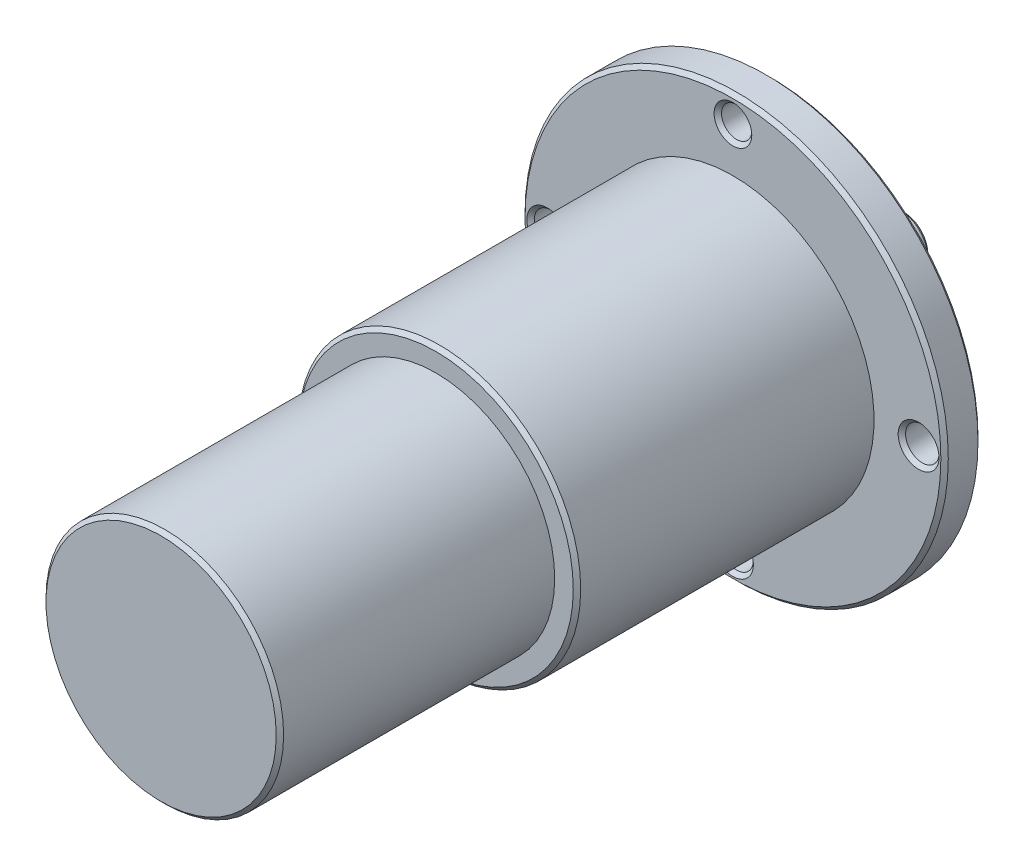
SolidWorks part; units mm, degrees
ref_plane "Front Plane" through (0, 0, 0) normal (0, 0, 1) x (1, 0, 0)
ref_plane "Top Plane" through (0, 0, 0) normal (0, 1, 0) x (1, 0, 0)
ref_plane "Right Plane" through (0, 0, 0) normal (1, 0, 0) x (0, 0, -1)
sketch "Sketch1" plane through (0, 0, 0) normal (0, 1, 0) x (1, 0, 0)
  line L0 (-29.6267, 29.8532) -> (-29.6267, -83.7972) construction
  line L1 (-29.6267, 24.6345) -> (-33.3767, 24.6345)
  line L2 (-33.3767, 9.6345) -> (-42.1267, 9.6345)
  line L3 (-42.1267, 9.6345) -> (-42.1267, 6.6345)
  line L4 (-42.1267, 6.6345) -> (-58.1267, 6.6345)
  line L5 (-58.1267, 6.6345) -> (-58.1267, 1.6345)
  line L6 (-58.1267, 1.6345) -> (-48.6267, 1.6345)
  line L7 (-48.6267, 1.6345) -> (-48.6267, -38.3655)
  line L8 (-48.6267, -38.3655) -> (-45.6267, -38.3655)
  line L9 (-45.6267, -38.3655) -> (-45.6267, -75.3655)
  line L10 (-45.6267, -75.3655) -> (-29.6267, -75.3655)
  line L11 (-33.3767, 24.6345) -> (-33.3767, 9.6345)
  line L12 (-29.6267, 24.6345) -> (-29.6267, -75.3655)
  dimension "D1" = 3.75
  dimension "D2" = 15
  dimension "D3" = 12.5
  dimension "D4" = 28.5
  dimension "D5" = 16
  dimension "D6" = 19
  dimension "D7" = 3
  dimension "D8" = 5
  dimension "D9" = 40
  dimension "D10" = 77
  dimension "D11" = 100
revolve "Revolve1" add sketch "Sketch1" angle 360 about L0
sketch "Sketch2" plane through (0, 0, -1.6345) normal (0, 0, 1) x (1, 0, 0)
  line L0 (-58.1267, 0) -> (-1.1267, 0) construction
  line L1 (-29.6267, 28.5) -> (-29.6267, -28.5) construction
  circle A1 centre (-4.6267, 0) radius 2.25
  circle A2 centre (-29.6267, 25) radius 2.0368
  circle A3 centre (-54.6267, 0) radius 2.25
  circle A4 centre (-29.6267, -25) radius 2.25
  dimension "D2" = 50
  dimension "D1" = 4.5
  dimension "D3" = 50
  dimension "D4" = 90
extrude "Cut-Extrude1" cut sketch "Sketch2" against normal blind 10
chamfer "Chamfer1" distance 0.5 angle 45 12 edges at (-52.3767, 0, -1.6345) (-2.3767, 0, -1.6345) (-27.5899, 25, -1.6345) (-27.3767, -25, -1.6345) (-31.6636, 25, -6.6345) (-6.8767, 0, -6.6345) (-31.8767, -25, -6.6345) (-56.8767, 0, -6.6345) (-42.1267, 0, -9.6345) (-33.3767, 0, -24.6345) (-58.1267, 0, -6.6345) (-58.1267, 0, -1.6345)
chamfer "Chamfer2" distance 0.5 angle 45 2 edges at (-45.6267, 0, 75.3655) (-48.6267, 0, 38.3655)
